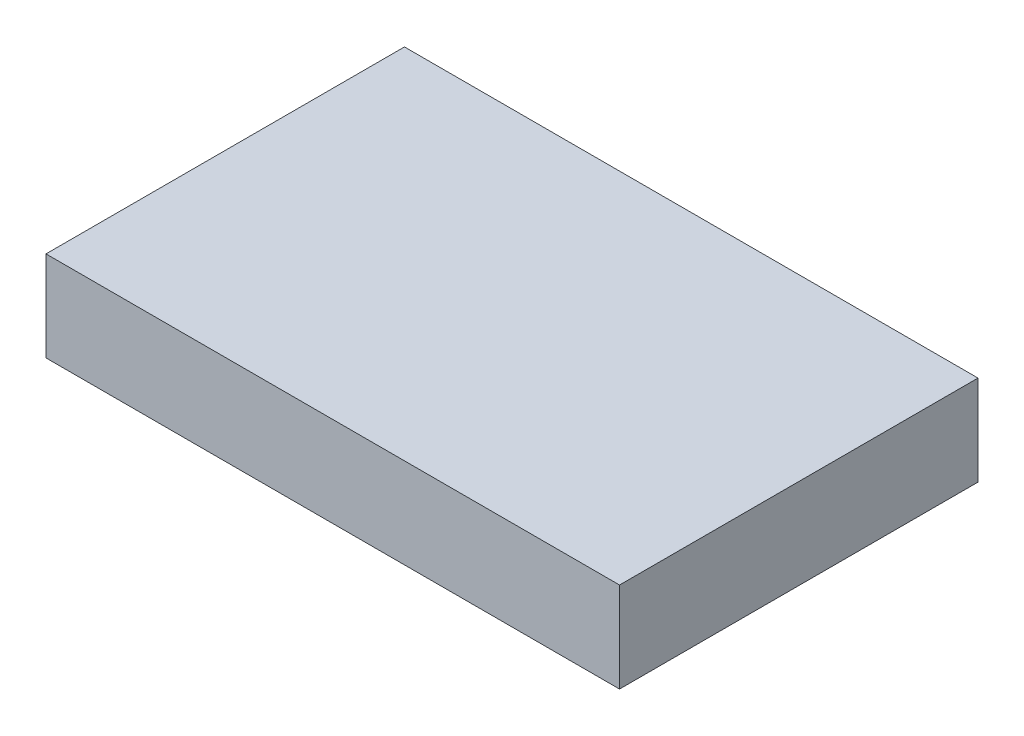
SolidWorks part; units mm, degrees
ref_plane "Ebene vorne" through (0, 0, 0) normal (0, 0, 1) x (1, 0, 0)
ref_plane "Ebene oben" through (0, 0, 0) normal (0, 1, 0) x (1, 0, 0)
ref_plane "Ebene rechts" through (0, 0, 0) normal (1, 0, 0) x (0, 0, -1)
sketch "Skizze1" plane through (0, 0, 0) normal (0, 1, 0) x (1, 0, 0)
  line L1 (-140, -87.5) -> (140, -87.5)
  line L2 (-140, -87.5) -> (-140, 87.5)
  line L3 (-140, 87.5) -> (140, 87.5)
  line L4 (140, -87.5) -> (140, 87.5)
  line L5 (-140, -87.5) -> (140, 87.5) construction
  line L6 (-140, 87.5) -> (140, -87.5) construction
  point P0 (0, 0)
  dimension "D1" = 280
  dimension "D2" = 175
extrude "Aufsatz-Linear austragen1" add sketch "Skizze1" along normal blind 44
sketch "Skizze2" plane through (0, 0, 87.5) normal (0, 0, 1) x (1, 0, 0)
  line L0 (-30.5606, 52.3888) -> (410.7727, 52.3888) construction
sketch "Skizze3" plane through (0, 0, -87.5) normal (0, 0, -1) x (-1, 0, 0)
  line L0 (-29.5085, 54.6041) -> (411.8248, 54.6041) construction
